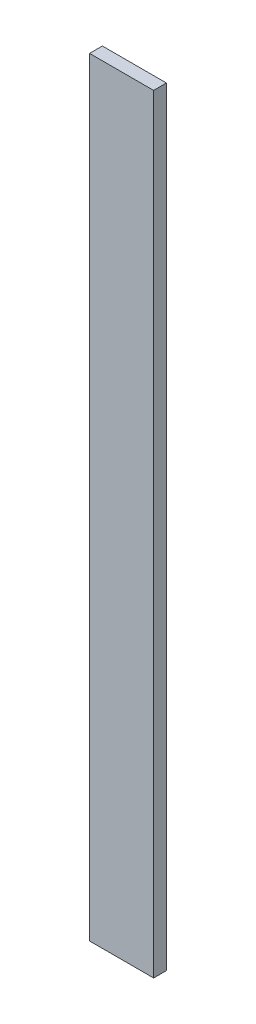
SolidWorks part; units mm, degrees
material "1.0037 (S235JR)"
ref_plane "Płaszczyzna przednia" through (0, 0, 0) normal (0, 0, 1) x (1, 0, 0)
ref_plane "Płaszczyzna górna" through (0, 0, 0) normal (0, 1, 0) x (1, 0, 0)
ref_plane "Płaszczyzna prawa" through (0, 0, 0) normal (1, 0, 0) x (0, 0, -1)
sketch "Szkic1" plane through (0, 0, 0) normal (0, 0, 1) x (1, 0, 0)
  line L1 (145, 640) -> (205, 640)
  line L2 (145, 640) -> (145, -80)
  line L3 (145, -80) -> (205, -80)
  line L4 (205, 640) -> (205, -80)
  line L5 (600, -80) -> (0, -80) construction
  line L6 (600, 640) -> (0, 640) construction
  line L10 (175, 560) -> (175, 640) construction
  line L11 (207, 560) -> (143, 560) construction
  dimension "D1" = 60
extrude "Dodanie-wyciągnięcie1" add sketch "Szkic1" along normal blind 12
sketch "Szkic2" plane through (0, 0, 12) normal (0, 0, 1) x (1, 0, 0)
  line L0 (175, 640) -> (175, -80) construction
  line L1 (205, 640) -> (145, 640) construction
  line L2 (145, -80) -> (205, -80) construction
